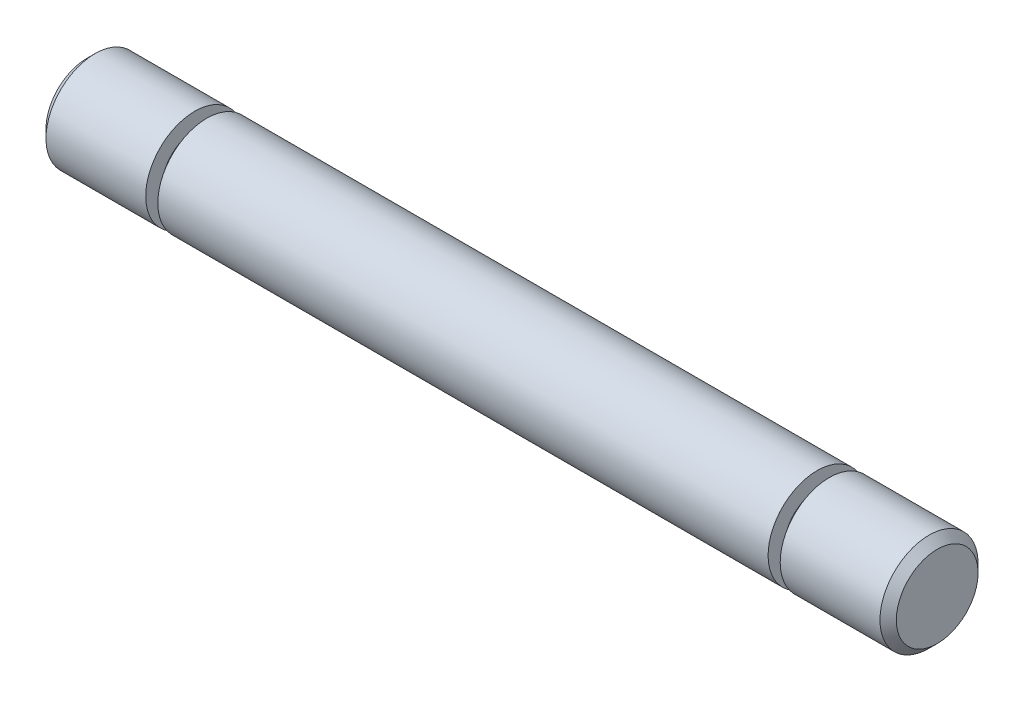
SolidWorks part; units mm, degrees
ref_plane "Plan de face" through (0, 0, 0) normal (0, 0, 1) x (1, 0, 0)
ref_plane "Plan de dessus" through (0, 0, 0) normal (0, 1, 0) x (1, 0, 0)
ref_plane "Plan de droite" through (0, 0, 0) normal (1, 0, 0) x (0, 0, -1)
sketch "Esquisse1" plane through (0, 0, 0) normal (0, 0, 1) x (1, 0, 0)
  line L0 (0, 0) -> (12.8037, 0) construction
  line L1 (0, 0) -> (0, 15.5366) construction
  line L2 (26, 0) -> (-26, 0)
  line L4 (-26, 0) -> (-26, 3)
  line L5 (-26, 3) -> (26, 3)
  line L6 (26, 0) -> (26, 3)
  point P10 (0, 0)
  dimension "D1" = 52
  dimension "D2" = 3
revolve "Révolution1" add sketch "Esquisse1" angle 360 about L0
chamfer "Chanfrein1" distance 0.5 angle 45 2 edges at (-26, 0, 3) (26, 0, 3)
sketch "Esquisse2" plane through (0, 0, 0) normal (0, 0, 1) x (1, 0, 0)
  line L0 (25.5, 3) -> (-25.5, 3) construction
  line L1 (25.5, 3) -> (-25.5, 3)
  line L3 (-9.5, 4) -> (-5.5, 4)
  line L4 (-9.5, 4) -> (-9.5, 2)
  line L5 (-9.5, 2) -> (-5.5, 2)
  line L6 (-5.5, 4) -> (-5.5, 2)
  line L7 (-9.5, 4) -> (-5.5, 2) construction
  line L8 (-9.5, 2) -> (-5.5, 4) construction
  point P2 (-7.5, 3)
  dimension "D1" = 1
  dimension "D2" = 7.5
  dimension "D3" = 4
extrude "Enlèv. mat.-Extru.1" [suppressed] cut sketch "Esquisse2" against normal through all both and the other way through all contours L5 L6 L3 L4
sketch "Esquisse3" plane through (0, 0, 0) normal (0, 0, 1) x (1, 0, 0)
  line L2 (25.5, 3) -> (-25.5, 3) construction
  line L3 (-19.4, 3) -> (-18.66, 3)
  line L4 (0, 0) -> (0, 10.3249) construction
  line L5 (-19.4, 3) -> (-19.4, 2)
  line L6 (-19.4, 2) -> (-18.66, 2)
  line L7 (-18.66, 3) -> (-18.66, 2)
  line L8 (18.66, 3) -> (18.66, 2)
  line L9 (19.4, 2) -> (18.66, 2)
  line L10 (19.4, 3) -> (19.4, 2)
  line L11 (19.4, 3) -> (18.66, 3)
  line L17 (0, 0) -> (-35.8372, 0) construction
  dimension "D1" = 0.74
  dimension "D2" = 2
  dimension "D3" = 38.8
revolve "Enlèvement de matière-Révolution1" cut sketch "Esquisse3" angle 360 about L17
